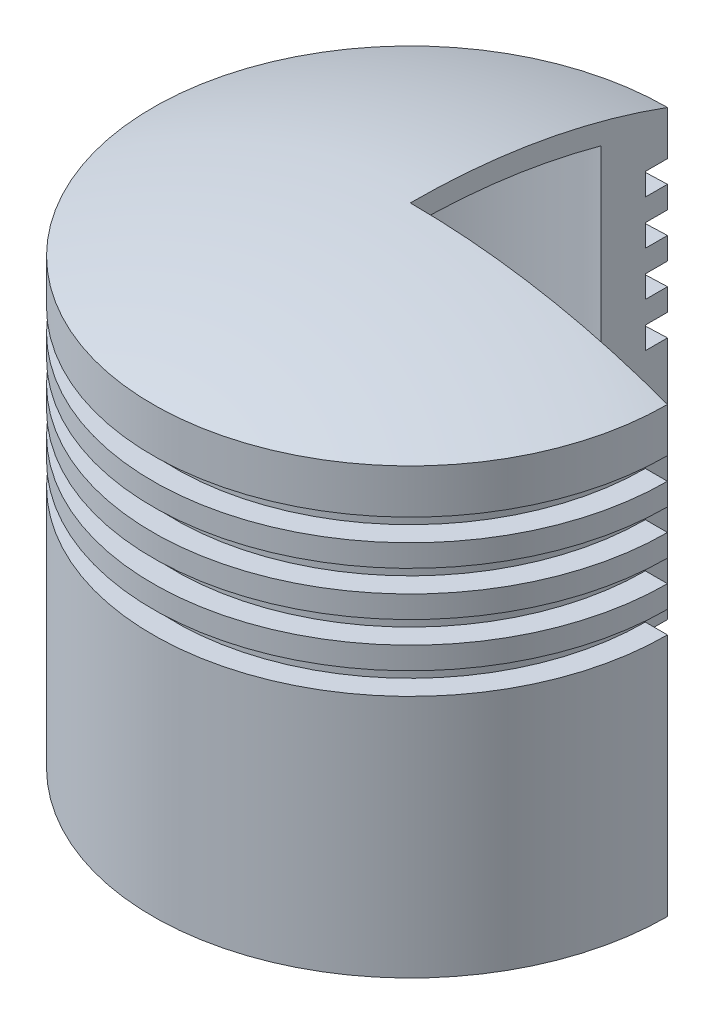
SolidWorks part; units mm, degrees
ref_plane "Front Plane" through (0, 0, 0) normal (0, 0, 1) x (1, 0, 0)
ref_plane "Top Plane" through (0, 0, 0) normal (0, 1, 0) x (1, 0, 0)
ref_plane "Right Plane" through (0, 0, 0) normal (1, 0, 0) x (0, 0, -1)
sketch "Sketch1" plane through (0, 0, 0) normal (0, 0, 1) x (1, 0, 0)
  line L0 (0, 598.0515) -> (0, 167.5828) construction
  line L1 (0, 167.5828) -> (0, 163)
  line L2 (43, 157.226) -> (43, 87.226)
  line L3 (58, 157.226) -> (58, 147.226)
  line L4 (58, 57.226) -> (50, 57.226)
  line L5 (50, 57.226) -> (50, 87.226)
  line L6 (43, 87.226) -> (50, 87.226)
  line L7 (58, 147.226) -> (53, 147.226)
  line L8 (53, 147.226) -> (53, 142.226)
  line L9 (53, 142.226) -> (58, 142.226)
  line L10 (58, 137.226) -> (53, 137.226)
  line L11 (53, 137.226) -> (53, 132.226)
  line L12 (53, 132.226) -> (58, 132.226)
  line L13 (58, 127.226) -> (53, 127.226)
  line L14 (53, 127.226) -> (53, 122.226)
  line L15 (53, 122.226) -> (58, 122.226)
  line L16 (58, 117.226) -> (53, 117.226)
  line L17 (53, 117.226) -> (53, 112.226)
  line L18 (53, 112.226) -> (58, 112.226)
  line L19 (58, 142.226) -> (58, 137.226)
  line L20 (58, 132.226) -> (58, 127.226)
  line L21 (58, 122.226) -> (58, 117.226)
  line L22 (58, 112.226) -> (58, 57.226)
  arc A0 (43, 157.226) -> (0, 163) centre (0, 0) ccw
  arc A1 (58, 157.226) -> (0, 167.5828) centre (0, 0) ccw
  dimension "D1" = 43
  dimension "D3" = 100
  dimension "D4" = 70
  dimension "D5" = 10
  dimension "D2" = 15
  dimension "D6" = 30
  dimension "D7" = 100
  dimension "D8" = 4
revolve "Revolve1" add sketch "Sketch1" angle 270 about L0
